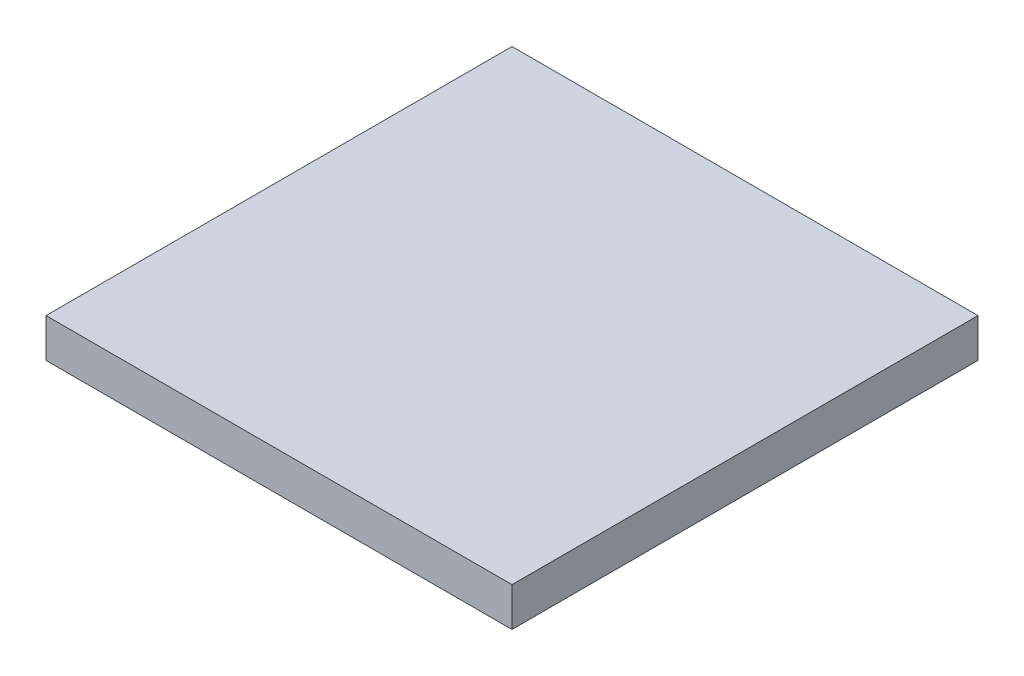
SolidWorks part; units mm, degrees
ref_plane "Спереди" through (0, 0, 0) normal (0, 0, 1) x (1, 0, 0)
ref_plane "Сверху" through (0, 0, 0) normal (0, 1, 0) x (1, 0, 0)
ref_plane "Справа" through (0, 0, 0) normal (1, 0, 0) x (0, 0, -1)
sketch "Эскиз2" plane through (0, 0, 0) normal (0, 1, 0) x (1, 0, 0)
  line L1 (-30, -30) -> (30, -30)
  line L2 (-30, -30) -> (-30, 30)
  line L3 (-30, 30) -> (30, 30)
  line L4 (30, -30) -> (30, 30)
  line L5 (-30, -30) -> (30, 30) construction
  line L6 (-30, 30) -> (30, -30) construction
  point P0 (0, 0)
  dimension "D1" = 60
  dimension "D2" = 60
extrude "Бобышка-Вытянуть1" add sketch "Эскиз2" along normal blind 5 contours L2 L3 L4 L1
